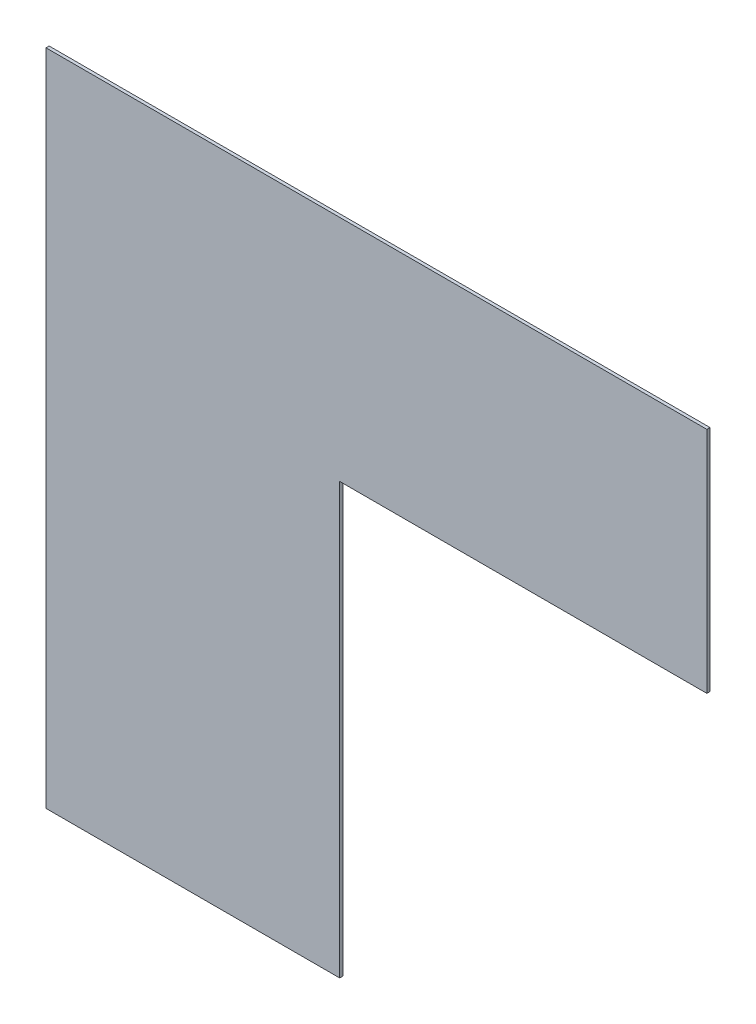
SolidWorks part; units mm, degrees
ref_plane "Plan de face" through (0, 0, 0) normal (0, 0, 1) x (1, 0, 0)
ref_plane "Plan de dessus" through (0, 0, 0) normal (0, 1, 0) x (1, 0, 0)
ref_plane "Plan de droite" through (0, 0, 0) normal (1, 0, 0) x (0, 0, -1)
sketch "Esquisse1" plane through (0, 0, 0) normal (0, 0, 1) x (1, 0, 0)
  line L0 (350, 628) -> (-280, 628)
  line L1 (0, 0) -> (-280, 0)
  line L2 (0, 0) -> (0, 410)
  line L3 (0, 410) -> (350, 410)
  line L4 (350, 628) -> (350, 410)
  line L5 (0, 528.9179) -> (0, -528.9179) construction
  line L6 (-494.0155, 0) -> (494.0155, 0) construction
  line L7 (-280, 628) -> (-280, 0)
  point P0 (0, 0)
  point P6 (0, 0)
  dimension "D1" = 630
  dimension "D2" = 628
  dimension "D3" = 218
  dimension "D4" = 350
extrude "Boss.-Extru.1" add sketch "Esquisse1" along normal blind 3
